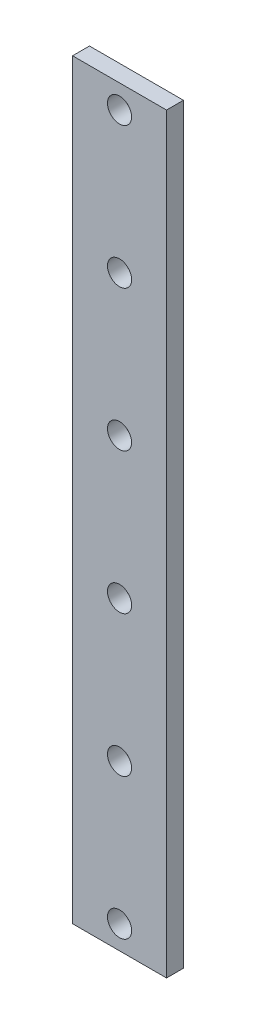
SolidWorks part; units mm, degrees
ref_plane "Front Plane" through (0, 0, 0) normal (0, 0, 1) x (1, 0, 0)
ref_plane "Top Plane" through (0, 0, 0) normal (0, 1, 0) x (1, 0, 0)
ref_plane "Right Plane" through (0, 0, 0) normal (1, 0, 0) x (0, 0, -1)
sketch "Sketch1" plane through (0, 0, 0) normal (0, 0, 1) x (1, 0, 0)
  line L1 (-6.35, 50.8) -> (6.35, 50.8)
  line L2 (-6.35, 50.8) -> (-6.35, -50.8)
  line L3 (-6.35, -50.8) -> (6.35, -50.8)
  line L4 (6.35, 50.8) -> (6.35, -50.8)
  line L5 (-6.35, 50.8) -> (6.35, -50.8) construction
  line L6 (-6.35, -50.8) -> (6.35, 50.8) construction
  point P0 (0, 0)
  dimension "D1" = 101.6
  dimension "D2" = 12.7
extrude "Boss-Extrude2" add sketch "Sketch1" along normal mid plane 2.286
hole_wizard "#4 Clearance Hole1" positions "Sketch4" profile "Sketch2" hole size "#4" standard "ANSI Inch" end condition through all
sketch "Sketch4" plane through (0, 0, 1.143) normal (0, 0, 1) x (1, 0, 0)
  line L0 (6.35, 50.8) -> (-6.35, 50.8) construction
  point P0 (0, 47.625)
  point P17 (0, 28.575)
  point P18 (0, 9.525)
  point P19 (0, -9.525)
  point P21 (0, 50.8)
  point P22 (0, -28.575)
  point P23 (0, -47.625)
  dimension "D1" = 3.175
  dimension "D2" = 6
sketch "Sketch2" plane through (0, 47.625, 1.143) normal (1, 0, 0) x (0, -1, 0)
  line L0 (0, 0) -> (0, 2.286)
  line L1 (0, 2.286) -> (1.6319, 2.286)
  line L2 (1.6319, 2.286) -> (1.6319, 0)
  line L5 (1.6319, 0) -> (0, 0)
  line L11 (0, -6.35) -> (0, 107.95) construction
  dimension "Thru Hole Dia." = 3.2639
  dimension "Thru Hole Depth" = 2.286
